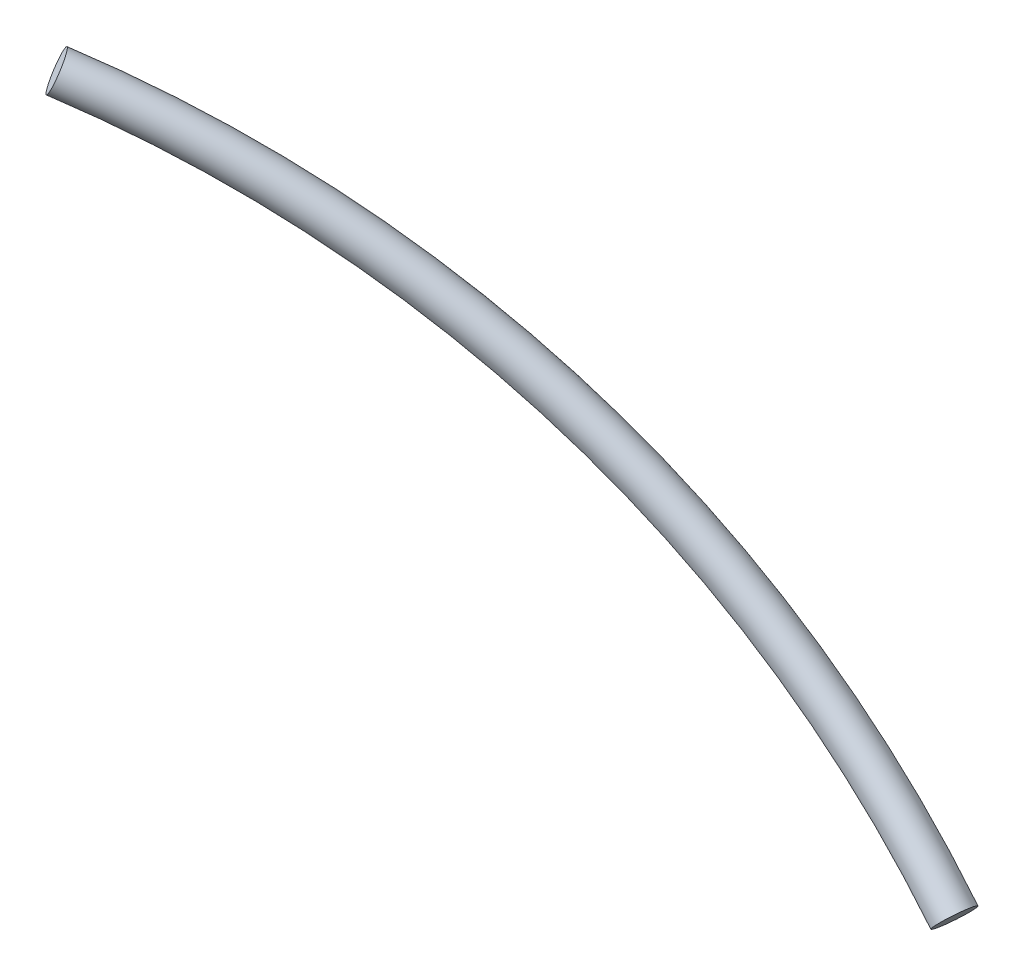
SolidWorks part; units mm, degrees
ref_plane "Front" through (0, 0, 0) normal (0, 0, 1) x (1, 0, 0)
ref_plane "Top" through (0, 0, 0) normal (0, 1, 0) x (1, 0, 0)
ref_plane "Right" through (0, 0, 0) normal (1, 0, 0) x (0, 0, -1)
ref_plane "Plane1" through (-240.7582, -278.0468, -126.2876) normal (-0.6191, -0.715, -0.3248) x (0.7853, -0.5637, -0.256)
sketch "Sketch1" plane through (-240.7582, -278.0468, -126.2876) normal (-0.6191, -0.715, -0.3248) x (0.7853, -0.5637, -0.256)
  line L0 (5353.3672, -16005.7301) -> (5644.3712, -16113.3361) construction
  line L1 (7736.8709, -15972.7648) -> (8090.9697, -15830.5765) construction
  line L2 (5353.3672, -16005.7301) -> (7736.8709, -15972.7648) construction
  line L3 (6548.1867, -16211.0458) -> (6545.1191, -15989.2474) construction
  arc A0 (5353.3672, -16005.7301) -> (7736.8709, -15972.7648) centre (6502.3711, -12898.4264) ccw
  point P6 (6548.1867, -16211.0458)
  dimension "D1" = 2438.4
  dimension "D3" = 1219.2
  dimension "D2" = 2743.2
  dimension "D4" = 221.8196
sketch "Sketch2" plane through (7787.0561, -4073.3124, -5877.2711) normal (0.7366, -0.3853, -0.5559) x (-0.4926, 0.2577, -0.8312)
  circle A0 centre (12261.9732, 4781.709) radius 50.8
  circle A1 centre (12261.9732, 4781.709) radius 50.8 construction
sweep "Sweep1" add profiles "Sketch2" path "Sketch1"
